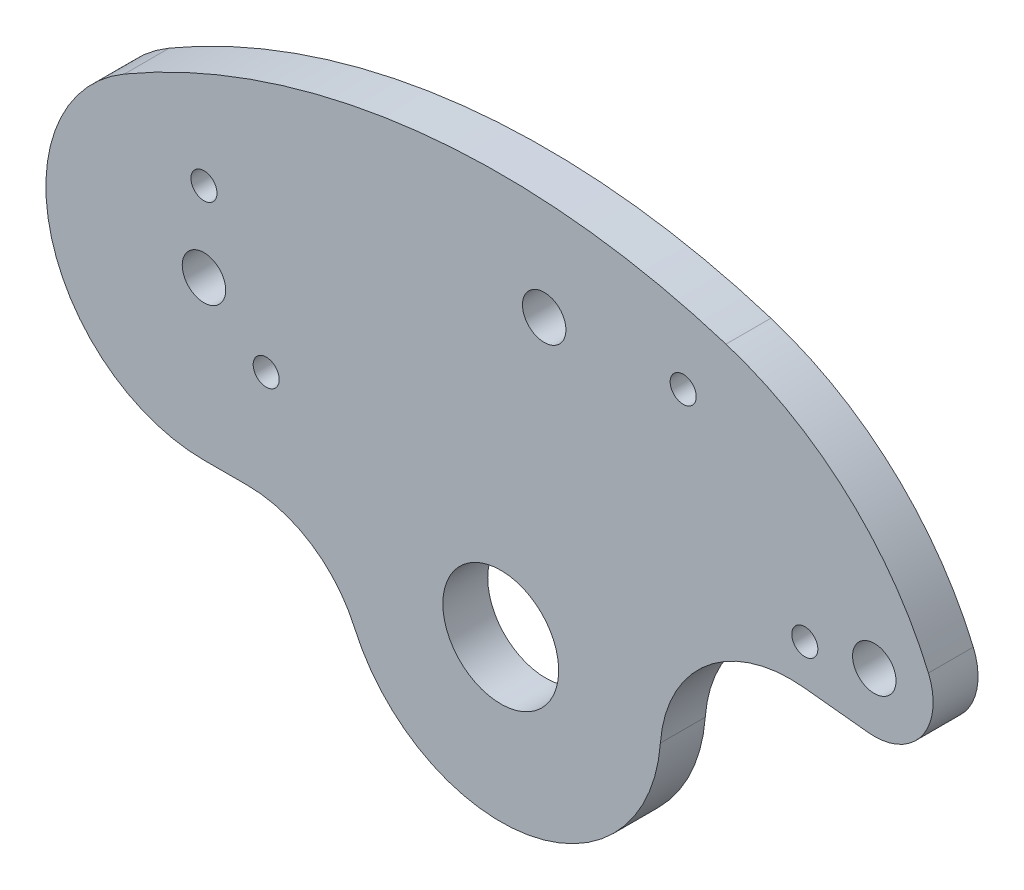
SolidWorks part; units mm, degrees
ref_plane "Front Plane" through (0, 0, 0) normal (0, 0, 1) x (1, 0, 0)
ref_plane "Top Plane" through (0, 0, 0) normal (0, 1, 0) x (1, 0, 0)
ref_plane "Right Plane" through (0, 0, 0) normal (1, 0, 0) x (0, 0, -1)
sketch "Sketch1" plane through (0, 0, 0) normal (0, 0, 1) x (1, 0, 0)
  line L2 (41.8893, 14.9006) -> (50.7468, 13.9657)
  line L4 (-35, 0.6662) -> (-41, 0.6662)
  circle A0 centre (-41, 22.5) radius 3
  circle A1 centre (6, 41.25) radius 3
  circle A2 centre (51.6, 22.05) radius 3
  circle A3 centre (0, 0) radius 8
  circle A4 centre (0, 0) radius 11 construction
  circle A5 centre (25.2, 42.25) radius 1.8
  circle A6 centre (-32.4, 15.5) radius 1.8
  circle A7 centre (42, 20.45) radius 1.8
  circle A8 centre (-41, 33.5) radius 1.8
  arc A9 (-20.2184, -8.9539) -> (-35, 0.6662) centre (-35, -15.5) ccw
  arc A10 (-20.2184, -8.9539) -> (22.0504, -1.6538) centre (0, 0) ccw
  arc A12 (41.8893, 14.9006) -> (22.0504, -1.6538) centre (40, -3) ccw
  arc A13 (50.7468, 13.9657) -> (59.077, 25.2403) centre (51.6, 22.05) ccw
  arc A14 (59.077, 25.2403) -> (31.1143, 50.6047) centre (17.5, 7.5) ccw
  arc A16 (31.1143, 50.6047) -> (-51.9872, 41.3678) centre (0, -47.9072) ccw
  arc A17 (-51.9872, 41.3678) -> (-41, 0.6662) centre (-41, 22.5) ccw
  dimension "D1" = 16
  dimension "D2" = 41.25
  dimension "D3" = 6
  dimension "D4" = 6
  dimension "D5" = 19.2
  dimension "D7" = 3.6
  dimension "D8" = 26.4
  dimension "D9" = 20.2
  dimension "D10" = 9.6
  dimension "D11" = 1.6
  dimension "D12" = 32.4
  dimension "D13" = 15.5
  dimension "D14" = 8.6
  dimension "D15" = 7
  dimension "D16" = 11
  dimension "D17" = 103.3088
  dimension "D18" = 18
  dimension "D6" = 1
  dimension "D19" = 40
  dimension "D20" = 3
  dimension "D21" = 35
  dimension "D22" = 15.5
  dimension "D23" = 17.5
  dimension "D24" = 7.5
extrude "Boss-Extrude1" add sketch "Sketch1" along normal blind 6.2
